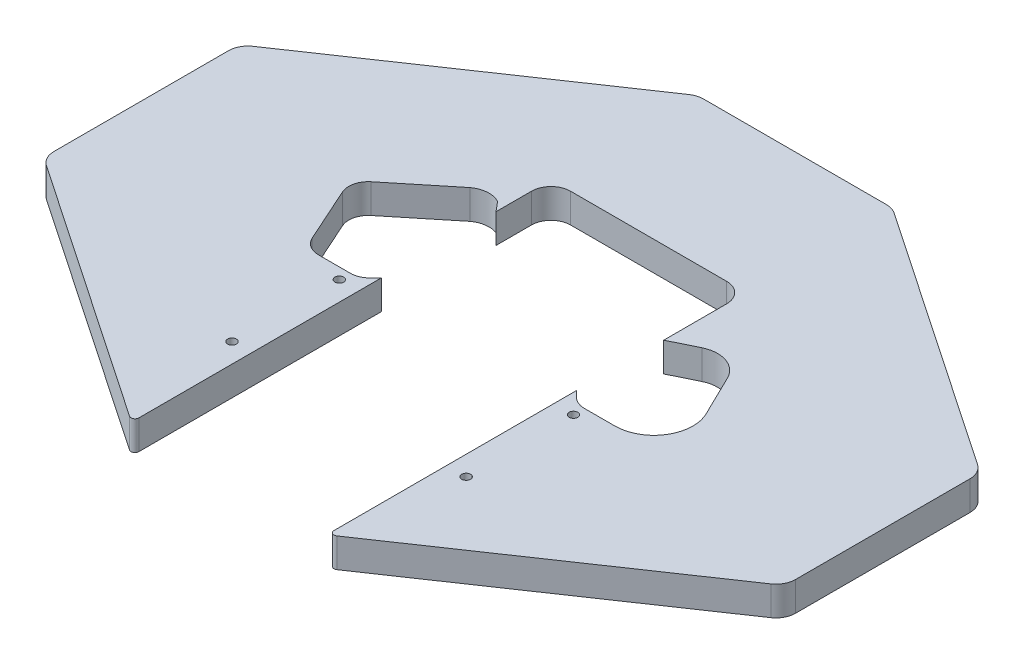
SolidWorks part; units mm, degrees
material "Balsa"
ref_plane "Plan de face" through (0, 0, 0) normal (0, 0, 1) x (1, 0, 0)
ref_plane "Plan de dessus" through (0, 0, 0) normal (0, 1, 0) x (1, 0, 0)
ref_plane "Plan de droite" through (0, 0, 0) normal (1, 0, 0) x (0, 0, -1)
sketch "Esquisse1" plane through (0, 0, 0) normal (0, 1, 0) x (1, 0, 0)
  line L0 (-76.6432, -51.4013) -> (63.3568, 43.5987)
  line L1 (63.3568, 43.5987) -> (163.3568, 43.5987)
  line L2 (-76.6432, -51.4013) -> (-76.6432, -151.4013)
  line L3 (63.3568, -246.4013) -> (163.3568, -246.4013)
  line L4 (303.3568, -51.4013) -> (303.3568, -151.4013)
  line L5 (163.3568, 43.5987) -> (303.3568, -51.4013)
  line L6 (163.3568, -246.4013) -> (303.3568, -151.4013)
  line L7 (-76.6432, -151.4013) -> (63.3568, -246.4013)
  point P0 (-76.6432, 43.5987)
  point P1 (303.3568, -246.4013)
  point P2 (-76.6432, -246.4013)
  point P3 (303.3568, 43.5987)
  dimension "D1" = 380
  dimension "D2" = 290
  dimension "D3" = 140
  dimension "D4" = 95
  dimension "D5" = 140
  dimension "D6" = 95
  dimension "D7" = 140
  dimension "D8" = 95
  dimension "D9" = 95
  dimension "D10" = 140
extrude "Boss.-Extru.1" add sketch "Esquisse1" along normal blind 15 contours L0 L1 L5 L4 L6 L3 L7 L2
sketch "Esquisse6" plane through (0, 0, 246.4013) normal (0, 0, 1) x (1, 0, 0)
  line L1 (63.3568, 15) -> (163.3568, 15)
  line L2 (63.3568, 15) -> (63.3568, 0)
  line L3 (63.3568, 0) -> (163.3568, 0)
  line L4 (163.3568, 15) -> (163.3568, 0)
extrude "Enlèv. mat.-Extru.1" cut sketch "Esquisse6" against normal blind 215
sketch "Esquisse11" plane through (0, 15, 0) normal (0, 1, 0) x (1, 0, 0)
  line L0 (63.3568, -31.4013) -> (63.3568, -246.4013) construction
  line L1 (163.3568, -31.4013) -> (163.3568, -246.4013) construction
  circle A0 centre (53.3568, -129.9013) radius 2.25
  circle A1 centre (53.3568, -184.9013) radius 2.25
  circle A2 centre (173.3568, -129.9013) radius 2.25
  circle A3 centre (173.3568, -184.9013) radius 2.25
  dimension "D1" = 4.5
  dimension "D2" = 4.5
  dimension "D6" = 4.5
  dimension "D7" = 4.5
  dimension "D3" = 55
  dimension "D4" = 10
  dimension "D5" = 55
  dimension "D8" = 10
  dimension "D9" = 10
  dimension "D10" = 10
  dimension "D11" = 61.5
  dimension "D12" = 61.5
sketch "Esquisse8" plane through (0, 15, 0) normal (0, 1, 0) x (1, 0, 0)
  line L4 (63.3568, -31.4013) -> (63.3568, -246.4013) construction
  line L5 (163.3568, -31.4013) -> (163.3568, -246.4013) construction
  circle A0 centre (180.3568, -120.9013) radius 2.25
  circle A1 centre (180.3568, -81.9013) radius 2.25
  circle A2 centre (46.3568, -120.9013) radius 2.25
  circle A3 centre (46.3568, -81.9013) radius 2.25
  dimension "D1" = 4.5
  dimension "D3" = 4.5
  dimension "D11" = 4.5
  dimension "D12" = 4.5
  dimension "D2" = 17
  dimension "D4" = 125.5
  dimension "D5" = 39
  dimension "D7" = 125.5
  dimension "D8" = 17
  dimension "D9" = 39
  dimension "D13" = 17
  dimension "D14" = 17
extrude "Enlèv. mat.-Extru.10" cut sketch "Esquisse11" against normal up to next
extrude "Enlèv. mat.-Extru.11" cut sketch "Esquisse8" against normal up to next
fillet "Congé10" radius 10 8 edges at (303.3568, 7.5, 151.4013) (303.3568, 7.5, 51.4013) (163.3568, 7.5, -43.5987) (63.3568, 7.5, -43.5987) (-76.6432, 7.5, 51.4013) (-76.6432, 7.5, 151.4013) (163.3568, 7.5, 31.4013) (63.3568, 7.5, 31.4013)
fillet "Congé11" radius 2 2 edges at (63.3568, 7.5, 246.4013) (163.3568, 7.5, 246.4013)
sketch "Esquisse12" plane through (0, 15, 0) normal (0, 1, 0) x (1, 0, 0)
  line L0 (46.0093, -55.5382) -> (18.0585, -78.3158)
  line L1 (15.2567, -90.1718) -> (27.9436, -118.3619)
  line L2 (59.1218, -54.5611) -> (63.3568, -59.5923)
  line L3 (63.3568, -41.4013) -> (63.3568, -242.6272) construction
  line L4 (60.4279, -121.3289) -> (63.3568, -118.4)
  line L5 (166.2857, -121.3289) -> (163.3568, -118.4)
  line L7 (37.0627, -124.2578) -> (53.3568, -124.2578)
  line L8 (63.3568, -118.4) -> (63.3568, -59.5923)
  line L9 (173.3568, -124.2578) -> (188.9489, -124.2578)
  line L10 (163.3568, -41.4013) -> (163.3568, -242.6272) construction
  line L11 (206.9248, -95.4904) -> (196.5197, -74.1568)
  line L12 (176.4622, -67.2505) -> (163.3568, -73.6424)
  line L13 (163.3568, -73.6424) -> (163.3568, -118.4)
  arc A0 (27.9436, -118.3619) -> (37.0627, -124.2578) centre (37.0627, -114.2578) ccw
  arc A1 (18.0585, -78.3158) -> (15.2567, -90.1718) centre (24.3757, -86.0678) ccw
  arc A2 (188.9489, -124.2578) -> (206.9248, -95.4904) centre (188.9489, -104.2578) ccw
  arc A3 (196.5197, -74.1568) -> (176.4622, -67.2505) centre (183.0378, -80.7324) ccw
  arc A4 (60.4279, -121.3289) -> (53.3568, -124.2578) centre (53.3568, -114.2578) cw
  arc A5 (173.3568, -124.2578) -> (166.2857, -121.3289) centre (173.3568, -114.2578) cw
  arc A7 (59.1218, -54.5611) -> (46.0093, -55.5382) centre (53.3568, -65.6688) ccw
  point P23 (63.3568, -41.4013)
  point P26 (163.3568, -124.2578)
  point P29 (63.3568, -124.2578)
  circle M3 centre (180.3568, -81.9013) radius 2.25
  circle M4 centre (180.3568, -120.9013) radius 2.25
  line M15 (163.3568, -41.4013) -> (163.3568, -242.6272)
  dimension "D1" = 10
  dimension "D2" = 20
  dimension "D3" = 15
extrude "Enlèv. mat.-Extru.12" cut sketch "Esquisse12" against normal up to next contours L11 L12 L9 M15 M3 M4 | L0 A1 L1 A0 L7 A4 L4 L8 L2 A7
